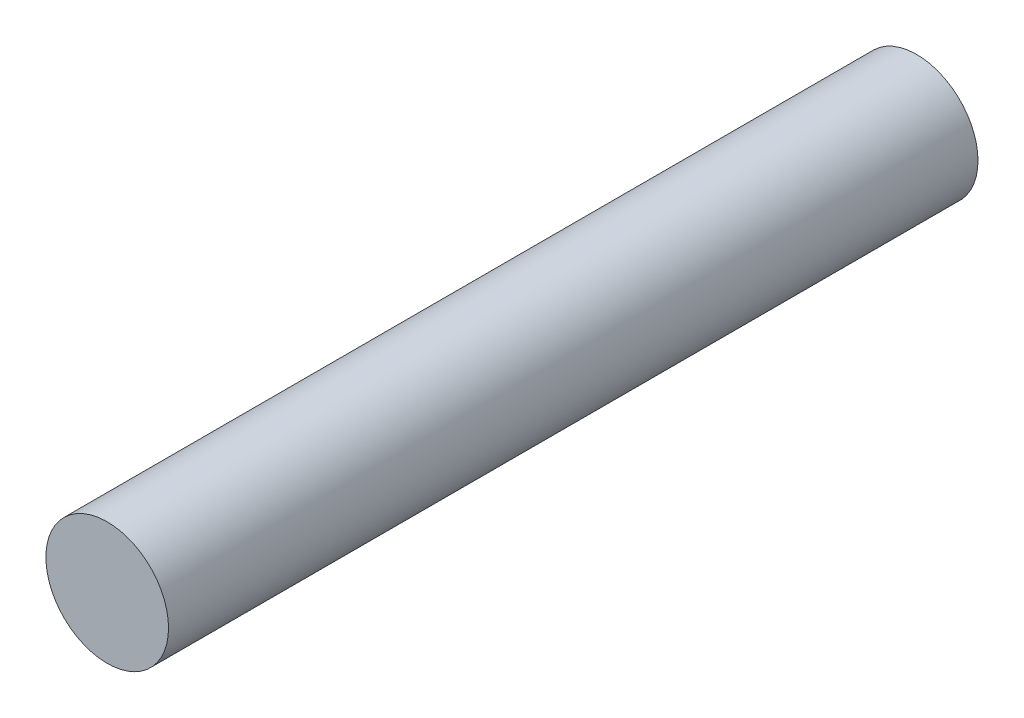
SolidWorks part; units mm, degrees
ref_plane "Front Plane" through (0, 0, 0) normal (0, 0, 1) x (1, 0, 0)
ref_plane "Top Plane" through (0, 0, 0) normal (0, 1, 0) x (1, 0, 0)
ref_plane "Right Plane" through (0, 0, 0) normal (1, 0, 0) x (0, 0, -1)
sketch "Sketch1" plane through (0, 0, 0) normal (0, 0, 1) x (1, 0, 0)
  circle A0 centre (0, 0) radius 2.5
extrude "Boss-Extrude1" add sketch "Sketch1" along normal blind 33
